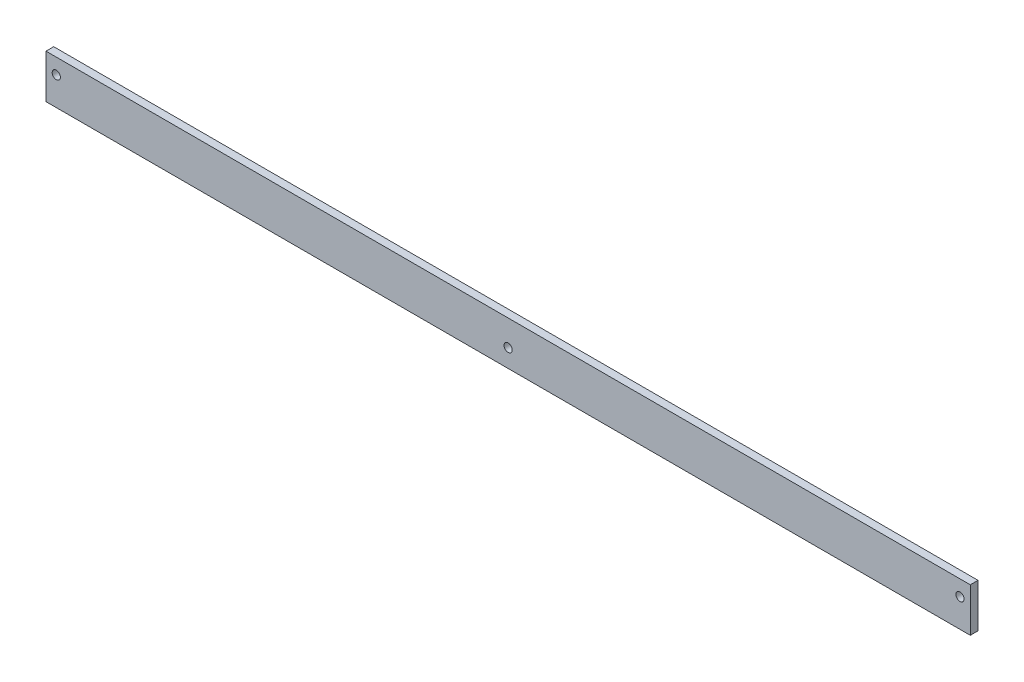
SolidWorks part; units mm, degrees
ref_plane "Plan de face" through (0, 0, 0) normal (0, 0, 1) x (1, 0, 0)
ref_plane "Plan de dessus" through (0, 0, 0) normal (0, 1, 0) x (1, 0, 0)
ref_plane "Plan de droite" through (0, 0, 0) normal (1, 0, 0) x (0, 0, -1)
sketch "Esquisse1" plane through (0, 0, 0) normal (0, 0, 1) x (1, 0, 0)
  line L1 (259.5, -8.5) -> (-99.5, -8.5)
  line L2 (259.5, -8.5) -> (259.5, 8.5)
  line L3 (259.5, 8.5) -> (-99.5, 8.5)
  line L4 (-99.5, -8.5) -> (-99.5, 8.5)
  line L5 (259.5, -11.5) -> (259.5, -8.5) construction
  point P0 (0, 0)
  dimension "D2" = 17
extrude "Boss.-Extru.1" add sketch "Esquisse1" along normal blind 3
sketch "Sketch1" plane through (0, 0, 0) normal (0, 0, -1) x (-1, 0, 0)
  circle A0 centre (95.5, 2.5) radius 1.6
extrude "Cut-Extrude1" cut sketch "Sketch1" against normal through all
sketch "Sketch2" plane through (0, 0, 0) normal (0, 0, -1) x (-1, 0, 0)
  circle A0 centre (-255.5, 2.5) radius 1.6
extrude "Cut-Extrude2" cut sketch "Sketch2" against normal through all
sketch "Sketch3" plane through (0, 0, 0) normal (0, 0, -1) x (-1, 0, 0)
  circle A0 centre (-80, -1.5) radius 1.6
extrude "Cut-Extrude3" cut sketch "Sketch3" against normal through all
